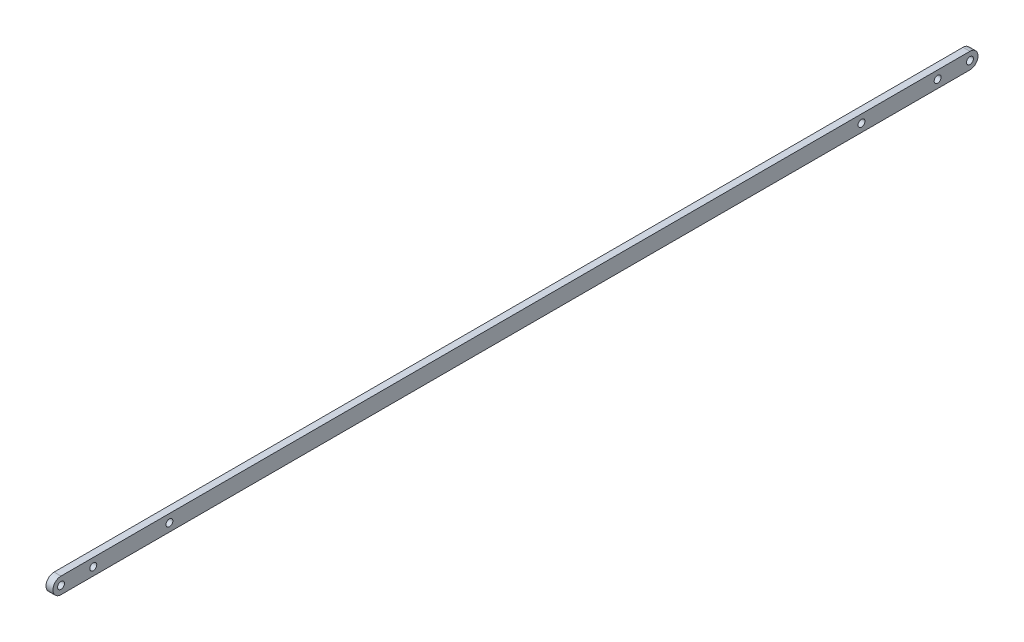
SolidWorks part; units mm, degrees
ref_plane "前视基准面" through (0, 0, 0) normal (0, 0, 1) x (1, 0, 0)
ref_plane "上视基准面" through (0, 0, 0) normal (0, 1, 0) x (1, 0, 0)
ref_plane "右视基准面" through (0, 0, 0) normal (1, 0, 0) x (0, 0, -1)
other "Configuration Table"
sketch "草图1" plane through (0, 0, 0) normal (1, 0, 0) x (0, 0, -1)
  line L0 (0, 5) -> (394, 5)
  line L5 (0, -2) -> (394, -2)
  line L6 (0, 3) -> (394, 3) construction
  line L7 (0, 0) -> (394, 0) construction
  arc A0 (0, 3) -> (0, 0) centre (0, 1.5) ccw
  arc A1 (394, 3) -> (394, 0) centre (394, 1.5) cw
  arc A2 (394, 5) -> (394, -2) centre (394, 1.5) cw
  arc A3 (0, 5) -> (0, -2) centre (0, 1.5) ccw
  arc A4 (394, 0) -> (394, 3) centre (394, 1.5) cw
  arc A5 (0, 3) -> (0, 0) centre (0, 1.5) cw
  circle A6 centre (14, 1.5) radius 1.5
  circle A7 centre (380, 1.5) radius 1.5
  circle A8 centre (47, 1.5) radius 1.5
  circle A9 centre (347, 1.5) radius 1.5
  dimension "D4" = 14
  dimension "D5" = 14
  dimension "D6" = 47
  dimension "D7" = 47
  dimension "D1" = 394
  dimension "D2" = 3
  dimension "D3" = 2
extrude "凸台-拉伸1" add sketch "草图1" along normal blind 3
